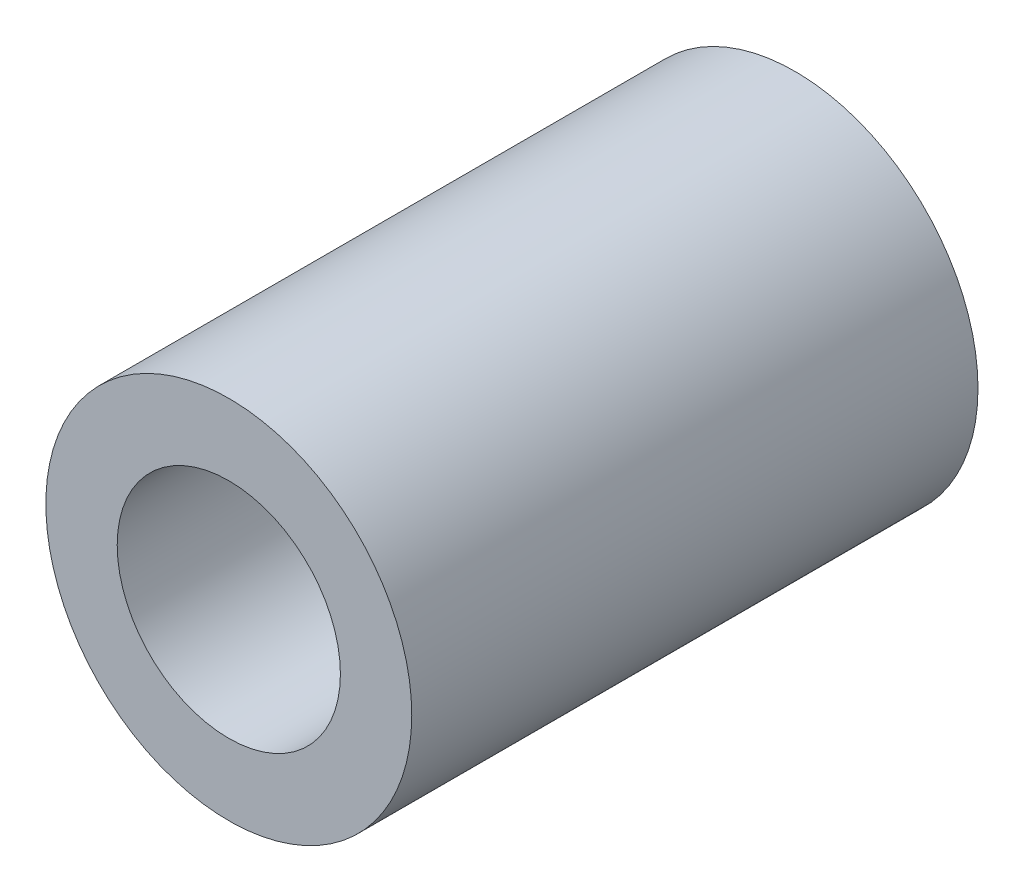
SolidWorks part; units mm, degrees
ref_plane "Plan de face" through (0, 0, 0) normal (0, 0, 1) x (1, 0, 0)
ref_plane "Plan de dessus" through (0, 0, 0) normal (0, 1, 0) x (1, 0, 0)
ref_plane "Plan de droite" through (0, 0, 0) normal (1, 0, 0) x (0, 0, -1)
sketch "Sketch1" plane through (0, 0, 0) normal (0, 0, 1) x (1, 0, 0)
  circle A0 centre (0, 0) radius 10
  circle A1 centre (0, 0) radius 6.1
  dimension "D1" = 20
  dimension "D2" = 12.2
extrude "Boss-Extrude1" add sketch "Sketch1" along normal mid plane 30.95
